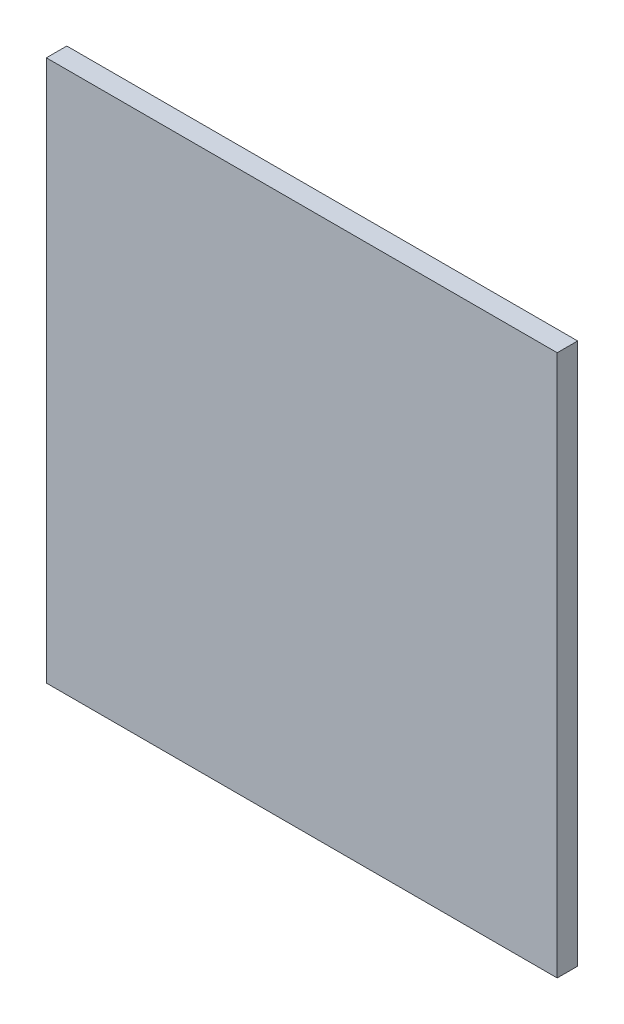
SolidWorks part; units mm, degrees
ref_plane "Plan de face" through (0, 0, 0) normal (0, 0, 1) x (1, 0, 0)
ref_plane "Plan de dessus" through (0, 0, 0) normal (0, 1, 0) x (1, 0, 0)
ref_plane "Plan de droite" through (0, 0, 0) normal (1, 0, 0) x (0, 0, -1)
sketch "Esquisse1" plane through (0, 0, 0) normal (0, 0, 1) x (1, 0, 0)
  line L1 (-250, 265) -> (250, 265)
  line L2 (-250, 265) -> (-250, -265)
  line L3 (-250, -265) -> (250, -265)
  line L4 (250, 265) -> (250, -265)
  line L5 (-250, 265) -> (250, -265) construction
  line L6 (-250, -265) -> (250, 265) construction
  point P0 (0, 0)
  dimension "D1" = 500
  dimension "D2" = 530
extrude "Boss.-Extru.1" add sketch "Esquisse1" along normal blind 20
